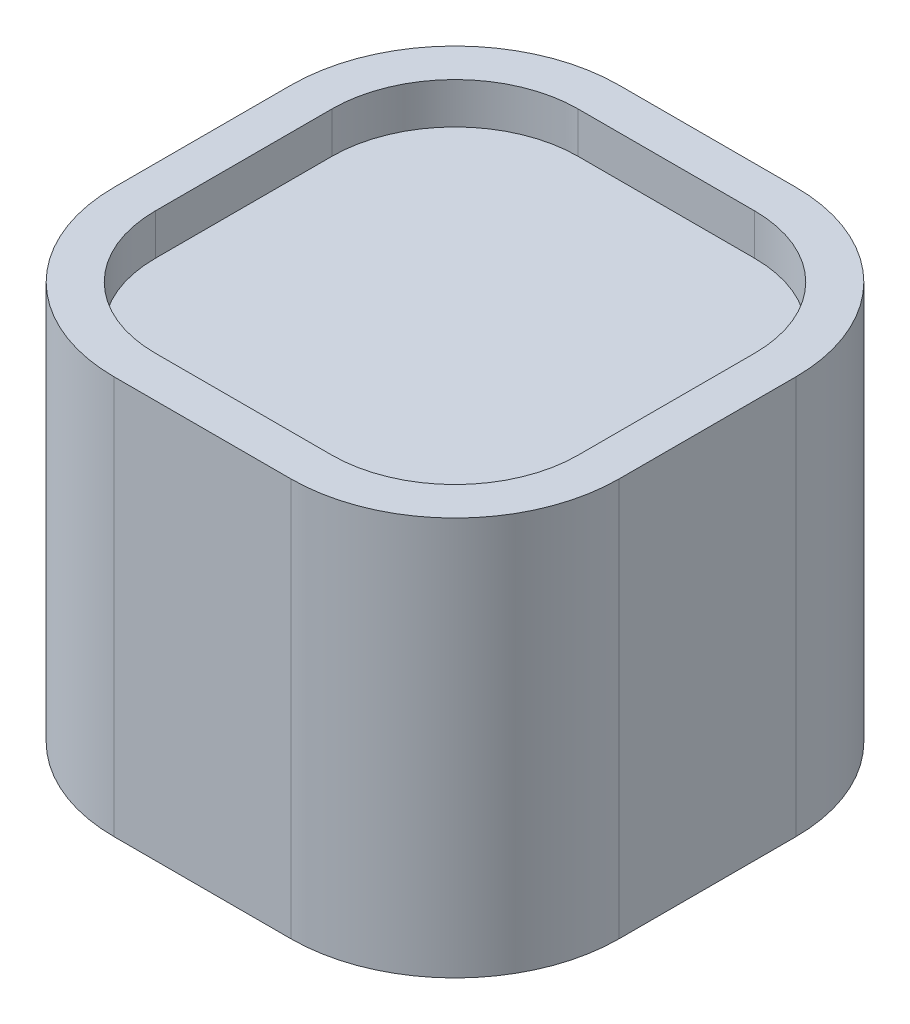
SolidWorks part; units mm, degrees
ref_plane "정면" through (0, 0, 0) normal (0, 0, 1) x (1, 0, 0)
ref_plane "윗면" through (0, 0, 0) normal (0, 1, 0) x (1, 0, 0)
ref_plane "우측면" through (0, 0, 0) normal (1, 0, 0) x (0, 0, -1)
sketch "스케치1" plane through (0, 0, 0) normal (0, 1, 0) x (1, 0, 0)
  line L1 (-61.5, 61.5) -> (61.5, 61.5)
  line L2 (-61.5, 61.5) -> (-61.5, -61.5)
  line L3 (-61.5, -61.5) -> (61.5, -61.5)
  line L4 (61.5, 61.5) -> (61.5, -61.5)
  line L5 (-61.5, 61.5) -> (61.5, -61.5) construction
  line L6 (-61.5, -61.5) -> (61.5, 61.5) construction
  point P0 (0, 0)
  dimension "D1" = 123
  dimension "D2" = 123
extrude "보스-돌출1" add sketch "스케치1" along normal blind 97
fillet "필렛1" radius 40 1 edges at (-61.5, 48.5, -61.5)
fillet "필렛2" radius 40 1 edges at (61.5, 48.5, -61.5)
fillet "필렛3" radius 40 1 edges at (61.5, 48.5, 61.5)
fillet "필렛4" radius 40 1 edges at (-61.5, 48.5, 61.5)
sketch "스케치2" plane through (0, 97, 0) normal (0, 1, 0) x (1, 0, 0)
  line L8 (-61.5, 21.5) -> (-61.5, -21.5)
  line L9 (-21.5, -61.5) -> (21.5, -61.5)
  line L10 (61.5, -21.5) -> (61.5, 21.5)
  line L11 (21.5, 61.5) -> (-21.5, 61.5)
  line L12 (-61.5, 21.5) -> (-61.5, -21.5)
  line L13 (-21.5, -61.5) -> (21.5, -61.5)
  line L14 (61.5, -21.5) -> (61.5, 21.5)
  line L15 (21.5, 61.5) -> (-21.5, 61.5)
  line L20 (-51.5, 21.5) -> (-51.5, -21.5)
  line L21 (-21.5, -51.5) -> (21.5, -51.5)
  line L22 (51.5, -21.5) -> (51.5, 21.5)
  line L23 (21.5, 51.5) -> (-21.5, 51.5)
  line L24 (-51.5, 21.5) -> (-51.5, -21.5)
  line L25 (-21.5, -51.5) -> (21.5, -51.5)
  line L26 (51.5, -21.5) -> (51.5, 21.5)
  line L27 (21.5, 51.5) -> (-21.5, 51.5)
  arc A8 (-61.5, -21.5) -> (-21.5, -61.5) centre (-21.5, -21.5) ccw
  arc A9 (21.5, -61.5) -> (61.5, -21.5) centre (21.5, -21.5) ccw
  arc A10 (61.5, 21.5) -> (21.5, 61.5) centre (21.5, 21.5) ccw
  arc A11 (-21.5, 61.5) -> (-61.5, 21.5) centre (-21.5, 21.5) ccw
  arc A12 (-61.5, -21.5) -> (-21.5, -61.5) centre (-21.5, -21.5) ccw
  arc A13 (21.5, -61.5) -> (61.5, -21.5) centre (21.5, -21.5) ccw
  arc A14 (61.5, 21.5) -> (21.5, 61.5) centre (21.5, 21.5) ccw
  arc A15 (-21.5, 61.5) -> (-61.5, 21.5) centre (-21.5, 21.5) ccw
  arc A20 (-51.5, -21.5) -> (-21.5, -51.5) centre (-21.5, -21.5) ccw
  arc A21 (21.5, -51.5) -> (51.5, -21.5) centre (21.5, -21.5) ccw
  arc A22 (51.5, 21.5) -> (21.5, 51.5) centre (21.5, 21.5) ccw
  arc A23 (-21.5, 51.5) -> (-51.5, 21.5) centre (-21.5, 21.5) ccw
  arc A24 (-51.5, -21.5) -> (-21.5, -51.5) centre (-21.5, -21.5) ccw
  arc A25 (21.5, -51.5) -> (51.5, -21.5) centre (21.5, -21.5) ccw
  arc A26 (51.5, 21.5) -> (21.5, 51.5) centre (21.5, 21.5) ccw
  arc A27 (-21.5, 51.5) -> (-51.5, 21.5) centre (-21.5, 21.5) ccw
  dimension "D1" = 0
  dimension "D2" = 10
extrude "컷-돌출1" cut sketch "스케치2" against normal blind 10 contours L27 A27 L24 A24 L25 A25 L26 A26
